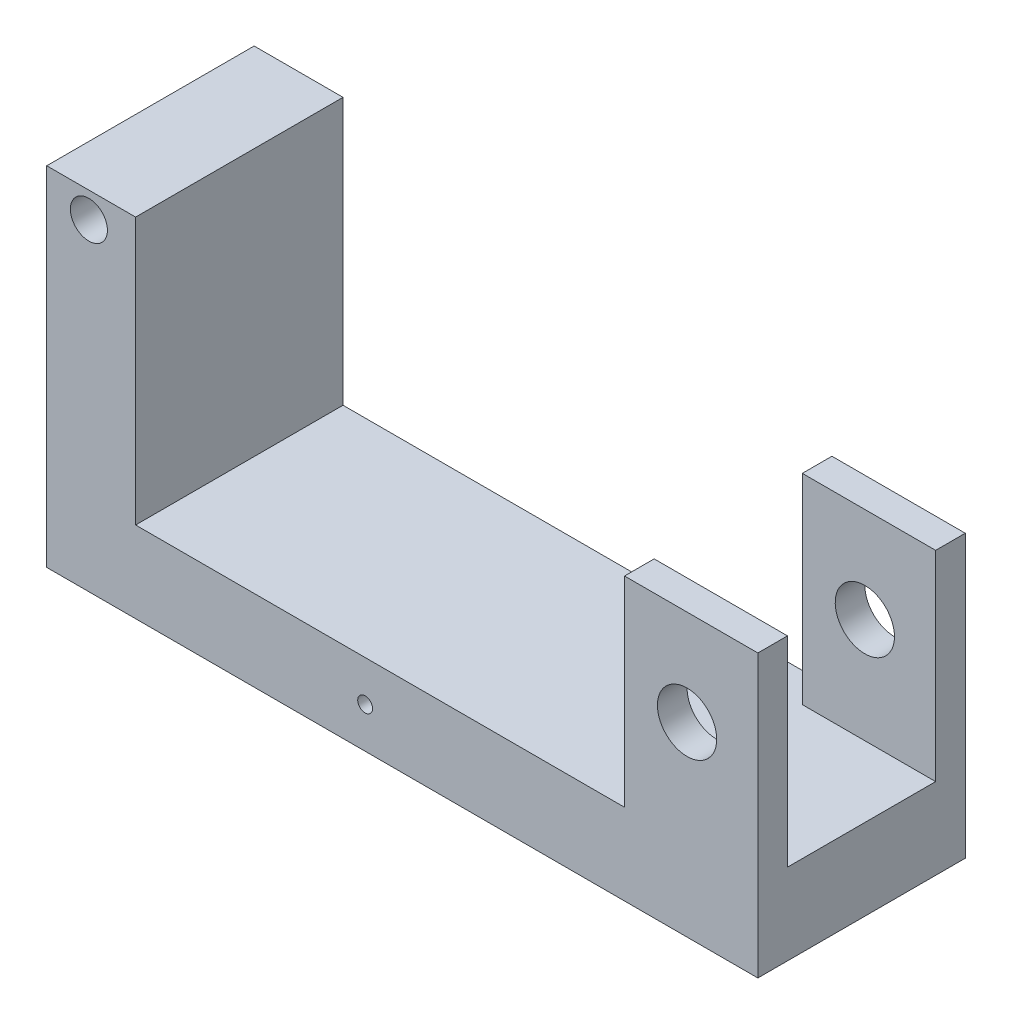
SolidWorks part; units mm, degrees
material "1060 Alloy"
ref_plane "Front Plane" through (0, 0, 0) normal (0, 0, 1) x (1, 0, 0)
ref_plane "Top Plane" through (0, 0, 0) normal (0, 1, 0) x (1, 0, 0)
ref_plane "Right Plane" through (0, 0, 0) normal (1, 0, 0) x (0, 0, -1)
sketch "Sketch1" plane through (0, 0, 0) normal (0, 0, 1) x (1, 0, 0)
  line L0 (-304.8, 0) -> (304.8, 0)
  line L1 (206.0721, 0) -> (-206.0721, 0) construction
  line L2 (-304.8, 0) -> (-304.8, 298.1966)
  line L3 (-304.8, 298.1966) -> (-228.6, 298.1966)
  line L4 (-228.6, 298.1966) -> (-228.6, 69.5966)
  line L5 (-228.6, 69.5966) -> (190.5, 69.5966)
  line L6 (190.5, 69.5966) -> (190.5, 241.3)
  line L7 (190.5, 241.3) -> (304.8, 241.3)
  line L8 (304.8, 241.3) -> (304.8, 0)
  point P2 (0, 0)
  dimension "D1" = 609.6
  dimension "D2" = 241.3
  dimension "D3" = 76.2
  dimension "D4" = 228.6
  dimension "D5" = 419.1
extrude "Boss-Extrude1" add sketch "Sketch1" along normal blind 177.8
sketch "Sketch3" plane through (0, 0, 177.8) normal (0, 0, 1) x (1, 0, 0)
  line L0 (-267.9571, 78.1117) -> (-268.9531, 357.51) construction
  line L1 (-267.9571, 78.1117) -> (-31.8674, 34.7983) construction
  line L2 (-145.3288, 81.4381) -> (-149.9122, 56.455) construction
  line L3 (-145.3288, 81.4381) -> (170.2935, 178.4668) construction
  line L4 (170.2935, 178.4668) -> (244.104, 159.5339) construction
  line L5 (0, 69.5966) -> (0, 0) construction
  line L6 (190.5, 69.5966) -> (-228.6, 69.5966) construction
  line L7 (-304.8, 0) -> (304.8, 0) construction
  circle A0 centre (244.104, 159.5339) radius 76.2 construction
  point P2 (170.2935, 178.4668)
  point P3 (244.104, 159.5339)
  point P4 (0, 34.7983)
  point P5 (-268.6632, 276.1964)
  point P6 (-145.3288, 81.4381)
  point P7 (-267.9571, 78.1117)
  point P12 (-31.8674, 34.7983)
  dimension "D1" = 76.2
  dimension "D2" = 240.03
  dimension "D3" = 279.4
  dimension "D4" = 330.2
  dimension "D5" = 25.4
sketch "Sketch4" plane through (0, 0, 177.8) normal (0, 0, 1) x (1, 0, 0)
  circle A0 centre (244.104, 159.5339) radius 25.4
  circle A1 centre (-268.6632, 276.1964) radius 15.875
  circle A2 centre (-31.8674, 34.7983) radius 6.35
  dimension "D1" = 50.8
  dimension "D2" = 31.75
  dimension "D3" = 12.7
extrude "Cut-Extrude1" cut sketch "Sketch4" against normal through all
sketch "Sketch5" plane through (190.5, 0, 0) normal (-1, 0, 0) x (0, 0, 1)
  line L6 (177.8, 69.5966) -> (0, 69.5966) construction
  line L7 (25.4, 69.5966) -> (152.4, 69.5966)
  line L8 (25.4, 69.5966) -> (25.4, 241.3)
  line L9 (25.4, 241.3) -> (152.4, 241.3)
  line L10 (152.4, 69.5966) -> (152.4, 241.3)
  line L11 (177.8, 241.3) -> (0, 241.3) construction
  line L13 (177.8, 241.3) -> (177.8, 69.5966) construction
  point P4 (88.9, 69.5966)
  dimension "D1" = 25.4
extrude "Cut-Extrude2" cut sketch "Sketch5" against normal through all
